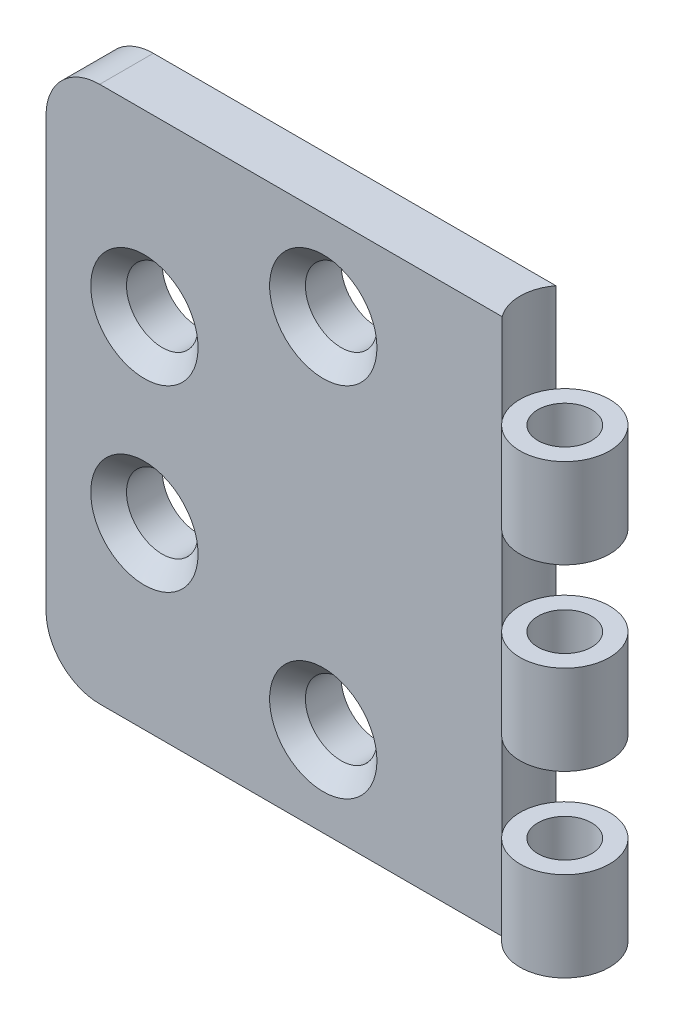
SolidWorks part; units mm, degrees
ref_plane "Спереди" through (0, 0, 0) normal (0, 0, 1) x (1, 0, 0)
ref_plane "Сверху" through (0, 0, 0) normal (0, 1, 0) x (1, 0, 0)
ref_plane "Справа" through (0, 0, 0) normal (1, 0, 0) x (0, 0, -1)
sketch "Эскиз1" plane through (0, 0, 0) normal (0, 0, 1) x (1, 0, 0)
  line L1 (-15, 15) -> (15, 15)
  line L2 (-15, 15) -> (-15, -15)
  line L3 (-15, -15) -> (15, -15)
  line L4 (15, 15) -> (15, -15)
  line L5 (-15, 15) -> (15, -15) construction
  line L6 (-15, -15) -> (15, 15) construction
  point P0 (0, 0)
  dimension "D1" = 30
  dimension "D2" = 30
extrude "Бобышка-Вытянуть1" add sketch "Эскиз1" along normal blind 3
sketch "Эскиз2" plane through (0, -15, 0) normal (0, -1, 0) x (1, 0, 0)
  line L0 (15, 1.5) -> (12.5, 1.5)
  line L1 (15, 3) -> (15, 0) construction
  line L2 (15, 1.5) -> (15, 3)
  line L3 (15, 3) -> (9.5, 3)
  line L4 (15, 0) -> (9.5, 0)
  line L7 (15, 0) -> (15, 1.5)
  circle A0 centre (12.5, 1.5) radius 2.5
  line M2 (-15, 0) -> (15, 0)
  line M3 (15, 0) -> (15, 3)
  line M4 (15, 3) -> (-15, 3)
  dimension "D1" = 5
  dimension "D2" = 2.5
extrude "Вырез-Вытянуть1" cut sketch "Эскиз2" against normal through all contours A0 M2 M3 | A0 M3 M4
sketch "Эскиз3" plane through (0, -15, 0) normal (0, -1, 0) x (1, 0, 0)
  circle A0 centre (12.5, 1.5) radius 2.5
extrude "Бобышка-Вытянуть3" add sketch "Эскиз3" against normal up to surface (30 mm away) up to face at (-0.125, 15, 1.5)
fillet "Скругление1" radius 3 2 edges at (-15, 15, 1.5) (-15, -15, 1.5)
sketch "Эскиз4" plane through (0, 0, 3) normal (0, 0, 1) x (1, 0, 0)
  line L0 (10.5, -15) -> (0.5, -15)
  line L1 (-12, -15) -> (10.5, -15) construction
  line L2 (0.5, -15) -> (0.5, 15)
  line L3 (10.5, 15) -> (-12, 15) construction
  line L4 (0.5, 15) -> (-9.5, 15)
  line L5 (-9.5, 15) -> (-9.5, -15)
  line L6 (0.5, 15) -> (0.5, 10)
  line L7 (-9.5, 15) -> (-9.5, 5)
  line L8 (0.5, 0) -> (-9.5, 0)
  circle A0 centre (0.5, 10) radius 2
  circle A1 centre (-9.5, 5) radius 2
  circle A2 centre (-9.5, -5) radius 2
  circle A3 centre (0.5, -10) radius 2
  dimension "D5" = 4
  dimension "D1" = 10
  dimension "D2" = 10
  dimension "D3" = 5
  dimension "D4" = 10
extrude "Вырез-Вытянуть2" cut sketch "Эскиз4" against normal through all contours A2 L5 | A2 L5 | A3 L2 | A3 L2 | L7 A1 L5 | L5 A1 L7 | L2 A0 | L2 A0
ref_plane "Плоскость1" through (0, -10, 0) normal (0, -1, 0) x (-1, 0, 0)
sketch "Эскиз6" plane through (0, -10, 0) normal (0, -1, 0) x (-1, 0, 0)
  circle A0 centre (-12.5, -1.5) radius 2.5
extrude "Вырез-Вытянуть3" cut sketch "Эскиз6" against normal blind 5
ref_plane "Плоскость2" through (0, 0, 0) normal (0, -1, 0) x (-1, 0, 0)
sketch "Эскиз7" plane through (0, 0, 0) normal (0, -1, 0) x (-1, 0, 0)
  circle A0 centre (-12.5, -1.5) radius 2.5
extrude "Вырез-Вытянуть4" cut sketch "Эскиз7" against normal blind 5
sketch "Эскиз8" plane through (0, 15, 0) normal (0, 1, 0) x (1, 0, 0)
  circle A0 centre (12.5, -1.5) radius 2.5
extrude "Вырез-Вытянуть5" cut sketch "Эскиз8" against normal blind 5
sketch "Эскиз9" plane through (0, -15, 0) normal (0, -1, 0) x (1, 0, 0)
  circle A0 centre (12.5, 1.5) radius 1.5
  dimension "D1" = 3
extrude "Вырез-Вытянуть6" cut sketch "Эскиз9" against normal through all
chamfer "Фаска1" distance 1 angle 45 4 edges at (2.5, 10, 3) (-7.5, 5, 3) (-7.5, -5, 3) (2.5, -10, 3)
